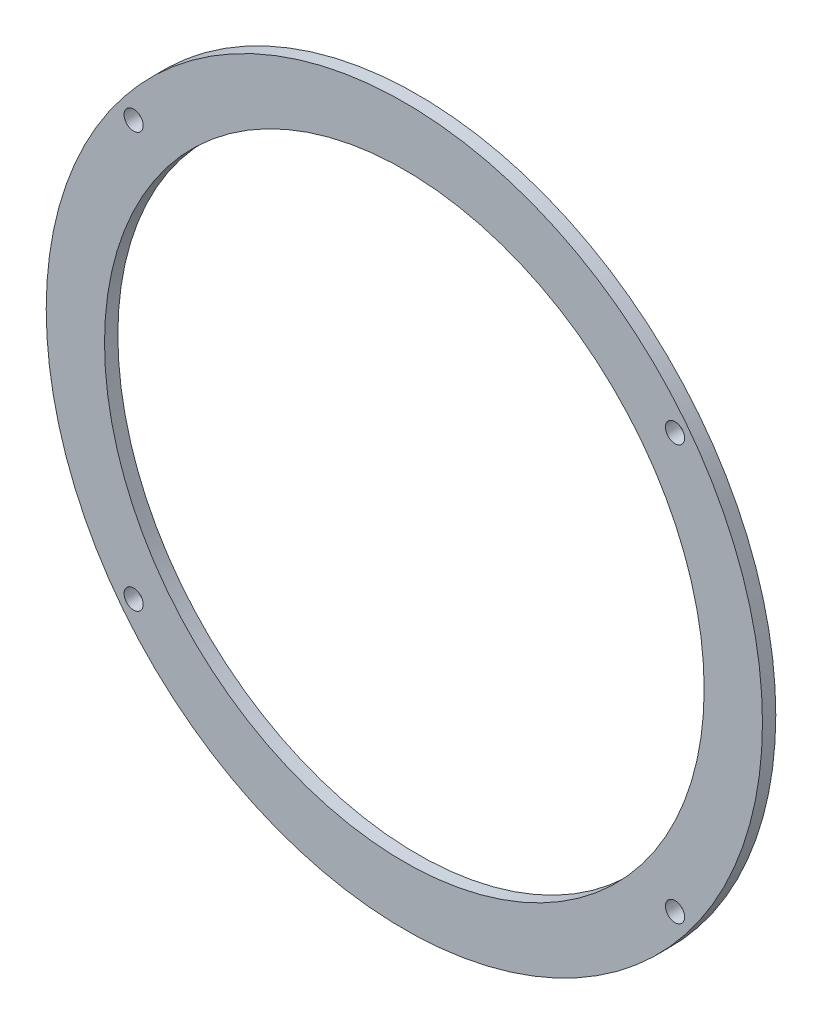
SolidWorks part; units mm, degrees
ref_plane "Front Plane" through (0, 0, 0) normal (0, 0, 1) x (1, 0, 0)
ref_plane "Top Plane" through (0, 0, 0) normal (0, 1, 0) x (1, 0, 0)
ref_plane "Right Plane" through (0, 0, 0) normal (1, 0, 0) x (0, 0, -1)
sketch "Sketch1" plane through (0, 0, 0) normal (0, 0, 1) x (1, 0, 0)
  line L0 (43, 0) -> (-43, 0) construction
  line L1 (0, -43) -> (0, 43) construction
  line L2 (32.5, -24.9) -> (-32.5, -24.9) construction
  line L3 (32.5, -24.9) -> (32.5, 24.9) construction
  line L4 (32.5, 24.9) -> (-32.5, 24.9) construction
  line L5 (-32.5, -24.9) -> (-32.5, 24.9) construction
  circle A1 centre (0, 0) radius 36
  circle A4 centre (0, 0) radius 43
  circle A5 centre (32.5, -24.9) radius 1.15
  circle A6 centre (-32.5, -24.9) radius 1.15
  circle A7 centre (-32.5, 24.9) radius 1.15
  circle A8 centre (32.5, 24.9) radius 1.15
  point P10 (32.5, 0)
  point P14 (0, 24.9)
extrude "Boss-Extrude2" add sketch "Sketch1" along normal blind 1.6 contours A5 | A6 | A1 | A4 | A7 | A8
sketch "Sketch4" plane through (0, 0, 0) normal (0, 0, -1) x (-1, 0, 0)
  line L0 (-43, 0) -> (43, 0) construction
  line L1 (0, 43) -> (0, -43) construction
  line L2 (0, 43) -> (0, 41.8) construction
  line L3 (0, 41.8) -> (0.7, 41.8) construction
  line L7 (4.5, 41.8) -> (4.5, 39.5) construction
  line L16 (0.7, 41.8) -> (1.9, 41.8)
  line L17 (0.7, 41.8) -> (0.7, 39.5)
  line L18 (0.7, 39.5) -> (1.9, 39.5)
  line L19 (1.9, 41.8) -> (1.9, 39.5)
  line L20 (3.3, 41.8) -> (4.5, 41.8)
  line L21 (3.3, 41.8) -> (3.3, 39.5)
  line L22 (3.3, 39.5) -> (4.5, 39.5)
  line L23 (4.5, 41.8) -> (4.5, 39.5)
  line L24 (1.9, 41.8) -> (3.3, 41.8) construction
  line L25 (-0.7, 39.5) -> (-1.9, 39.5)
  line L26 (-1.9, 41.8) -> (-1.9, 39.5)
  line L27 (-0.7, 41.8) -> (-1.9, 41.8)
  line L28 (-0.7, 41.8) -> (-0.7, 39.5)
  line L29 (-3.3, 39.5) -> (-4.5, 39.5)
  line L30 (-4.5, 41.8) -> (-4.5, 39.5)
  line L31 (-3.3, 41.8) -> (-4.5, 41.8)
  line L32 (-3.3, 41.8) -> (-3.3, 39.5)
  circle A2 centre (0, 0) radius 43 construction
  point P18 (0, 43)
  point P24 (0, 0)
  point P27 (0, 0)
extrude "Boss-Extrude3" add sketch "Sketch4" along normal blind 0.1
